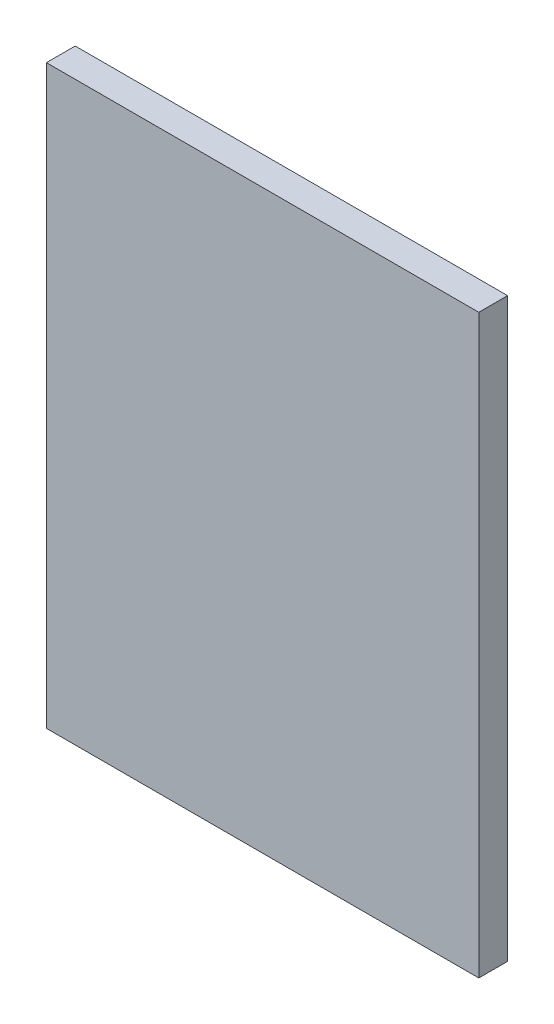
SolidWorks part; units mm, degrees
ref_plane "Front Plane" through (0, 0, 0) normal (0, 0, 1) x (1, 0, 0)
ref_plane "Top Plane" through (0, 0, 0) normal (0, 1, 0) x (1, 0, 0)
ref_plane "Right Plane" through (0, 0, 0) normal (1, 0, 0) x (0, 0, -1)
sketch "Sketch1" plane through (0, 0, 0) normal (0, 0, 1) x (1, 0, 0)
  line L1 (-7.5, -10) -> (7.5, -10)
  line L2 (-7.5, -10) -> (-7.5, 10)
  line L3 (-7.5, 10) -> (7.5, 10)
  line L4 (7.5, -10) -> (7.5, 10)
  line L5 (-7.5, -10) -> (7.5, 10) construction
  line L6 (-7.5, 10) -> (7.5, -10) construction
  point P0 (0, 0)
extrude "Boss-Extrude1" add sketch "Sketch1" against normal blind 1
ref_plane "Plane_1" through (0, 0, 0) normal (0, 0, 1) x (1, 0, 0)
sketch "Sketch2" plane through (0, 0, 0) normal (0, 0, 1) x (1, 0, 0)
  line L1 (-4.875, -6) -> (4.875, -6)
  line L2 (-4.875, -6) -> (-4.875, 6)
  line L3 (-4.875, 6) -> (4.875, 6)
  line L4 (4.875, -6) -> (4.875, 6)
  line L5 (-4.875, -6) -> (4.875, 6) construction
  line L6 (-4.875, 6) -> (4.875, -6) construction
  point P0 (0, 0)
extrude "Boss-Extrude2" add sketch "Sketch2" against normal blind 2
